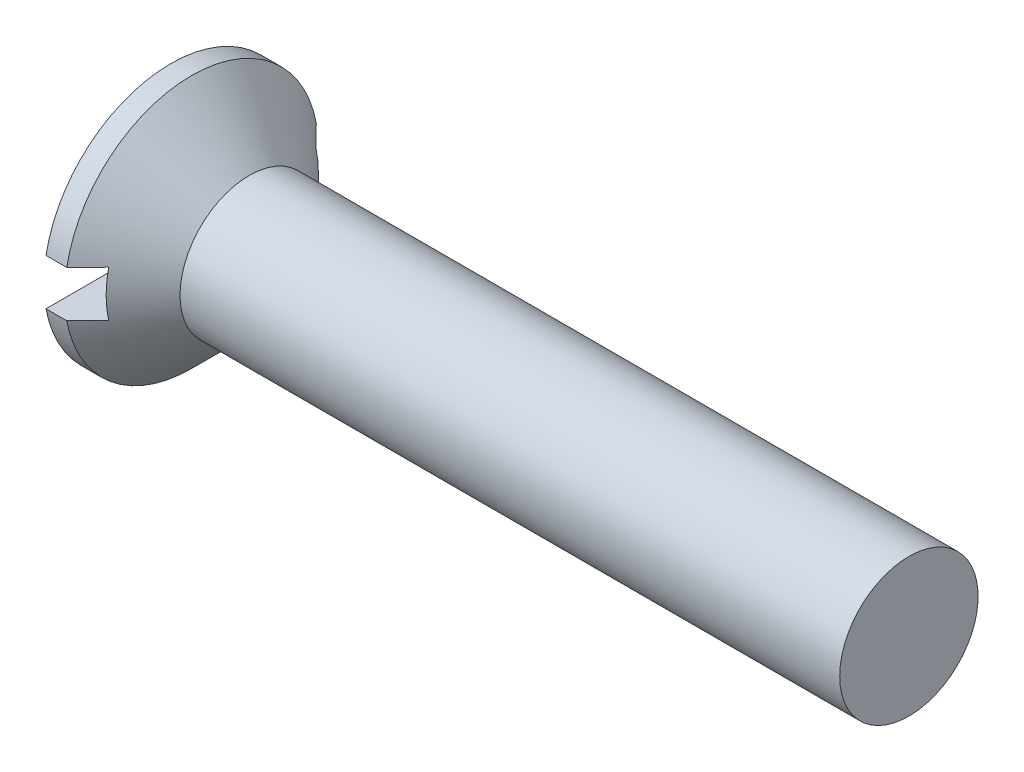
SolidWorks part; units mm, degrees
ref_plane "Plane1" through (0, 0, 0) normal (0, 0, 1) x (1, 0, 0)
ref_plane "Plane2" through (0, 0, 0) normal (0, 1, 0) x (1, 0, 0)
ref_plane "Plane3" through (0, 0, 0) normal (1, 0, 0) x (0, 0, -1)
sketch "BodySke" plane through (0, 0, 0) normal (0, 0, 1) x (1, 0, 0)
  line L0 (0, 0) -> (0, 2.75)
  line L1 (0, 2.75) -> (0.45, 2.75)
  line L2 (1.7, 1.5) -> (16, 1.5)
  line L3 (16, 1.5) -> (16, 0)
  line L4 (16, 0) -> (0, 0)
  line L5 (-6.35, 0) -> (82.55, 0) construction
  line L6 (1.7, -1.5) -> (16, -1.5) construction
  line L7 (0.45, -2.75) -> (1.7, -1.5) construction
  line L8 (0.45, 2.75) -> (1.7, 1.5)
  line L9 (0, -2.75) -> (0.45, -2.75) construction
  line L10 (2.2, 3.0875) -> (2.2, -6.4375) construction
  line L11 (0, 6.35) -> (0, -3.175) construction
  dimension "Diameter" = 3
  dimension "Length" = 16
  dimension "Head_ht" = 1.7
  dimension "Head_dia" = 5.5
  dimension "Head_ang" = 90
  dimension "D6" = 0.45
  dimension "Advance" = 0.5
  dimension "Thread_nom" = 16
revolve "Base-Revolve" add sketch "BodySke" angle 360 about L5
cosmetic thread "ThreadCosmetic" [suppressed] parameters "Thread_length"=13.8, "Thread_minor"=2.439
sketch "Sketch2" plane through (0, 0, 0) normal (-1, 0, 0) x (0, 0, 1)
  line L0 (-2.75, -0.5) -> (2.75, -0.5)
  line L1 (-2.75, -0.5) -> (-2.75, 0.5)
  line L2 (2.75, 0.5) -> (-2.75, 0.5)
  line L3 (2.75, 0.5) -> (2.75, -0.5)
  dimension "D1" = 0.5
  dimension "Slot_width" = 1
  dimension "D2" = 5.5
  dimension "D3" = 2.75
extrude "Slot" cut sketch "Sketch2" against normal blind 0.9
sketch "Sketch3" plane through (0, 0, 0) normal (-1, 0, 0) x (0, 0, 1)
  line L0 (-0.395, 1.55) -> (0.395, 1.55)
  line L1 (0.395, 1.55) -> (0.395, -1.55)
  line L2 (0.395, -1.55) -> (-0.395, -1.55)
  line L3 (-0.395, -1.55) -> (-0.395, 1.55)
  dimension "D1" = 1.55
  dimension "Cross_dia" = 3.1
  dimension "D2" = 0.395
  dimension "Cross_width" = 0.79
ref_plane "Plane4" through (2.08, 0, 0) normal (-1, 0, 0) x (0, 0, 1)
sketch "Sketch4" plane through (2.08, 0, 0) normal (-1, 0, 0) x (0, 0, 1)
  line L0 (-0.1975, 0.1975) -> (0.1975, 0.1975)
  line L3 (0.1975, 0.1975) -> (0.1975, -0.1975)
  line L4 (0.1975, -0.1975) -> (-0.1975, -0.1975)
  line L5 (-0.1975, -0.1975) -> (-0.1975, 0.1975)
  dimension "D1" = 0.395
  dimension "D2" = 0.395
  dimension "D3" = 0.1975
  dimension "D4" = 0.1975
loft "Cross" [suppressed] cut profiles "Sketch3", "Sketch4"
pattern_circular "CirPattern1" [suppressed] count 2 every 90 about axis through (-6.35, 0, 0) along (1, 0, 0)
sketch "ThdSchSke" plane through (0, 0, 0) normal (0, 0, 1) x (1, 0, 0)
  line L0 (2.2, -1.2195) -> (2.0036, -1.5)
  line L1 (2.2, -1.2195) -> (2.3964, -1.5)
  line L2 (2.3964, -1.5) -> (2.3964, -1.875)
  line L3 (-3.175, 0) -> (5.1513, 0) construction
  line L5 (2.3964, -1.875) -> (2.0036, -1.875)
  line L6 (2.0036, -1.875) -> (2.0036, -1.5)
  line L7 (0, 2.75) -> (0, 0.5) construction
  dimension "Thread_minor" = 2.439
  dimension "Diameter" = 3
  dimension "Start" = 2.2
  dimension "SideAngle" = 55
  dimension "VeeAngle" = 70
  dimension "Overcut" = 3.75
revolve "ThreadSchematic" [suppressed] cut sketch "ThdSchSke" angle 360 about L3
pattern_linear "ThdSchPat" [suppressed]
equation "\"D1@Sketch3\" = \"Cross_dia@Sketch3\" / 2"
equation "\"D2@Sketch3\" = \"Cross_width@Sketch3\" / 2"
equation "\"D1@Sketch4\" = \"Cross_width@Sketch3\" *.5"
equation "\"D2@Sketch4\" = \"D1@Sketch4\""
equation "\"D4@Sketch4\" = \"D2@Sketch4\" / 2"
equation "\"D3@Sketch4\" = \"D1@Sketch4\" / 2"
equation "\"D1@Sketch2\" = \"Slot_width@Sketch2\" / 2"
equation "\"D2@Sketch2\" = \"Head_dia@BodySke\""
equation "\"D3@Sketch2\" = \"D2@Sketch2\" / 2"
equation "\"Thread_length@ThreadCosmetic\" = ((sgn( (\"Length@BodySke\" - \"Advance@BodySke\" - \"Head_ht@BodySke\" ) - \"Thread_nom@BodySke\" )-1)*( (\"Length@BodySke\" - \"Advance@BodySke\" - \"Head_ht@BodySke\" ) - \"Thread_nom@BodySke\" ))/-2+ \"Thread_nom@BodySke\""
equation "\"Thread_minor@ThdSchSke\" = \"Thread_minor@ThreadCosmetic\""
equation "\"Diameter@ThdSchSke\" = \"Diameter@BodySke\""
equation "\"Overcut@ThdSchSke\" = \"Diameter@BodySke\" * 1.25"
equation "\"Start@ThdSchSke\" = 0.000001 + \"Length@BodySke\" - \"Thread_length@ThreadCosmetic\"  '---Countersunk---"
equation "\"Num_threads@ThdSchPat\" = int( \"Thread_length@ThreadCosmetic\" / \"Advance@BodySke\" + 0.999 )  + 1"
equation "\"Advance@ThdSchPat\" = \"Thread_length@ThreadCosmetic\" /  (\"Num_threads@ThdSchPat\" - 1) 'relax it"
